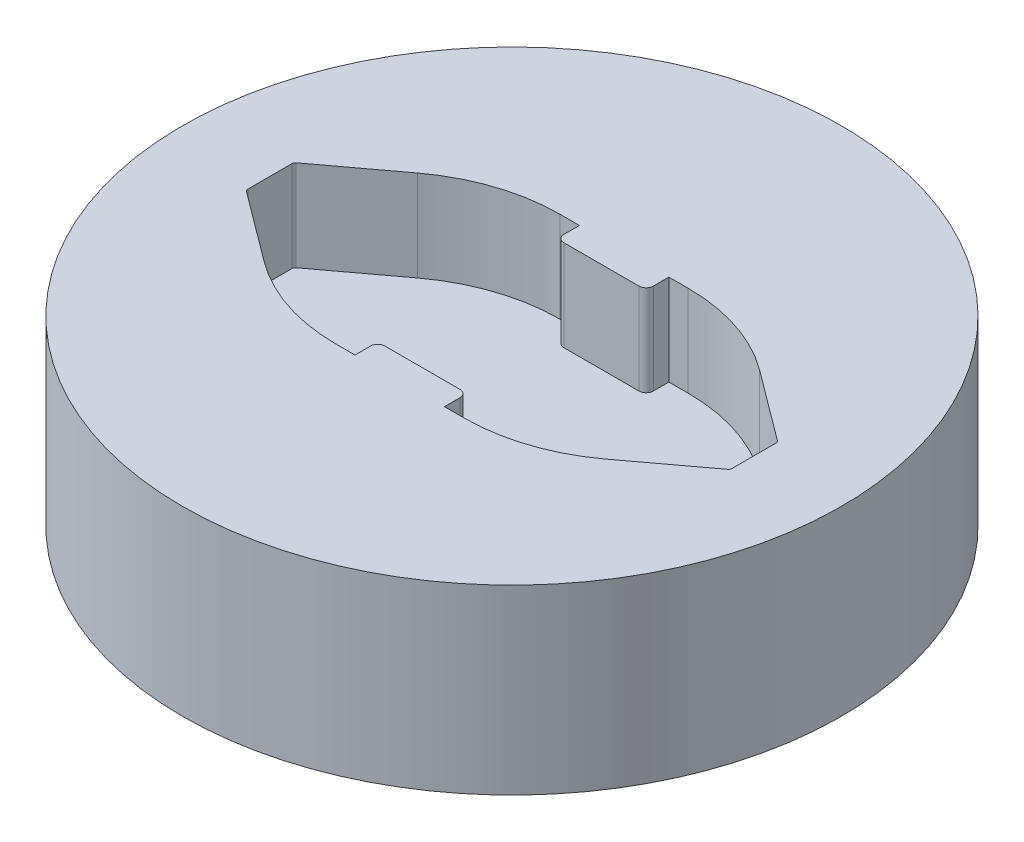
SolidWorks part; units mm, degrees
material "Polyurethane Foam Flexible"
ref_plane "Front Plane" through (0, 0, 0) normal (0, 0, 1) x (1, 0, 0)
ref_plane "Top Plane" through (0, 0, 0) normal (0, 1, 0) x (1, 0, 0)
ref_plane "Right Plane" through (0, 0, 0) normal (1, 0, 0) x (0, 0, -1)
sketch "Sketch1" plane through (0, 0, 0) normal (0, 1, 0) x (1, 0, 0)
  circle A0 centre (0, 0) radius 92.075
  dimension "D1" = 184.15
extrude "Boss-Extrude1" add sketch "Sketch1" along normal blind 50.8
sketch "Sketch2" plane through (0, 50.8, 0) normal (0, 1, 0) x (1, 0, 0)
  line L0 (-67.6118, 6.1497) -> (-67.6118, 4.9888)
  line L1 (-47.8012, 21.4284) -> (-67.2097, 6.9513)
  line L2 (-17.906, 31.35) -> (-12.5, 31.35)
  line L3 (-12.5, 31.35) -> (-12.5, 27)
  line L4 (-0.6678, 25) -> (-10.5, 25)
  line L5 (10.5, 25) -> (0.6678, 25)
  line L6 (12.5, 31.35) -> (12.5, 27)
  line L7 (12.5, 31.35) -> (17.906, 31.35)
  line L8 (67.2097, 6.9513) -> (47.8012, 21.4284)
  line L9 (67.6118, 4.9888) -> (67.6118, 6.1497)
  line L10 (67.6118, -6.1497) -> (67.6118, -4.9888)
  line L11 (47.8012, -21.4284) -> (67.2097, -6.9513)
  line L12 (17.906, -31.35) -> (12.5, -31.35)
  line L13 (12.5, -31.35) -> (12.5, -27)
  line L14 (0.6678, -25) -> (10.5, -25)
  line L15 (-10.5, -25) -> (-0.6678, -25)
  line L16 (-12.5, -31.35) -> (-12.5, -27)
  line L17 (-12.5, -31.35) -> (-17.906, -31.35)
  line L18 (-67.2097, -6.9513) -> (-47.8012, -21.4284)
  line L19 (-67.6118, -4.9888) -> (-67.6118, -6.1497)
  line L20 (-0.6678, 25) -> (0.6678, 25)
  line L21 (-0.6678, -25) -> (0.6678, -25)
  line L22 (67.6118, -4.9888) -> (67.6118, 4.9888)
  line L23 (-67.6118, -4.9888) -> (-67.6118, 4.9888)
  line L24 (0, 25) -> (0, -25) construction
  line L25 (-67.6118, 0) -> (67.6118, 0) construction
  arc A0 (-67.2097, 6.9513) -> (-67.6118, 6.1497) centre (-66.6118, 6.1497) ccw
  arc A1 (-17.906, 31.35) -> (-47.8012, 21.4284) centre (-17.906, -18.65) ccw
  arc A2 (-12.5, 27) -> (-10.5, 25) centre (-10.5, 27) ccw
  arc A3 (10.5, 25) -> (12.5, 27) centre (10.5, 27) ccw
  arc A4 (47.8012, 21.4284) -> (17.906, 31.35) centre (17.906, -18.65) ccw
  arc A5 (67.6118, 6.1497) -> (67.2097, 6.9513) centre (66.6118, 6.1497) ccw
  arc A6 (67.2097, -6.9513) -> (67.6118, -6.1497) centre (66.6118, -6.1497) ccw
  arc A7 (17.906, -31.35) -> (47.8012, -21.4284) centre (17.906, 18.65) ccw
  arc A8 (12.5, -27) -> (10.5, -25) centre (10.5, -27) ccw
  arc A9 (-10.5, -25) -> (-12.5, -27) centre (-10.5, -27) ccw
  arc A10 (-47.8012, -21.4284) -> (-17.906, -31.35) centre (-17.906, 18.65) ccw
  arc A11 (-67.6118, -6.1497) -> (-67.2097, -6.9513) centre (-66.6118, -6.1497) ccw
extrude "Cut-Extrude1" cut sketch "Sketch2" against normal blind 25.4
